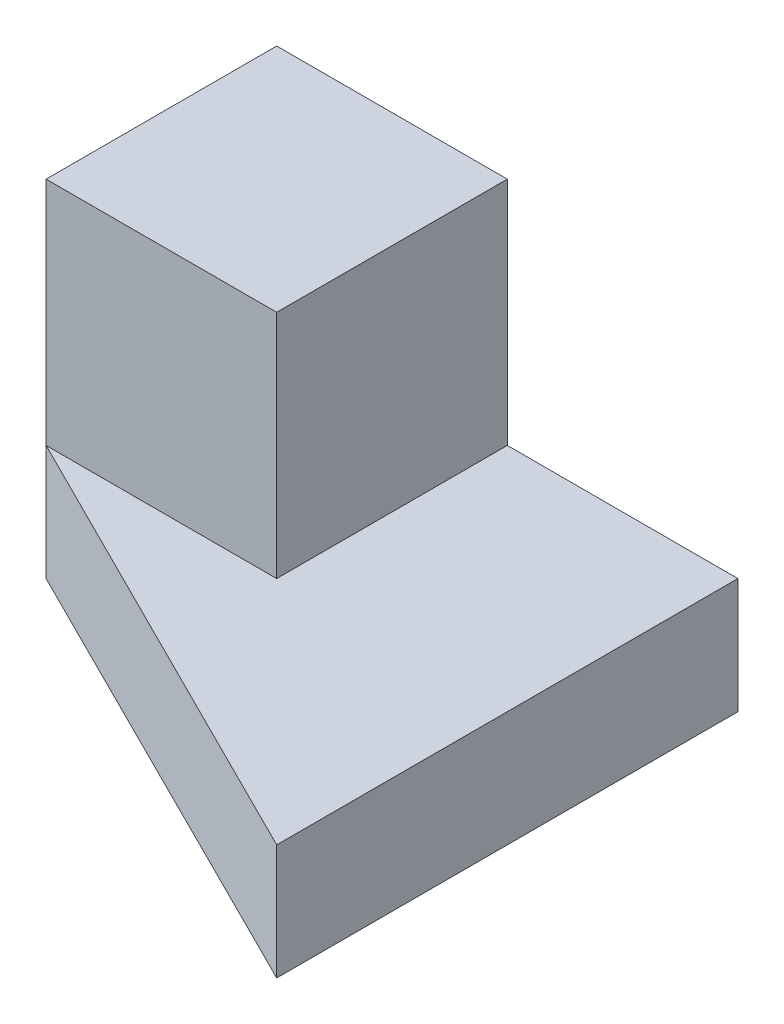
SolidWorks part; units mm, degrees
ref_plane "Front Plane" through (0, 0, 0) normal (0, 0, 1) x (1, 0, 0)
ref_plane "Top Plane" through (0, 0, 0) normal (0, 1, 0) x (1, 0, 0)
ref_plane "Right Plane" through (0, 0, 0) normal (1, 0, 0) x (0, 0, -1)
sketch "Sketch1" plane through (0, 0, 0) normal (0, 1, 0) x (1, 0, 0)
  line L0 (0, 0) -> (0, 40)
  line L1 (0, 40) -> (-40, 40)
  line L2 (-40, 40) -> (-40, 20)
  line L3 (-40, 20) -> (0, 0)
  dimension "D1" = 40
  dimension "D2" = 40
  dimension "D3" = 20
extrude "Boss-Extrude1" add sketch "Sketch1" along normal blind 10
sketch "Sketch2" plane through (0, 10, 0) normal (0, 1, 0) x (1, 0, 0)
  line L1 (-40, 40) -> (-20, 40)
  line L2 (-40, 40) -> (-40, 20)
  line L3 (-40, 20) -> (-20, 20)
  line L4 (-20, 40) -> (-20, 20)
  dimension "D1" = 20
  dimension "D2" = 20
extrude "Boss-Extrude2" add sketch "Sketch2" along normal blind 20
